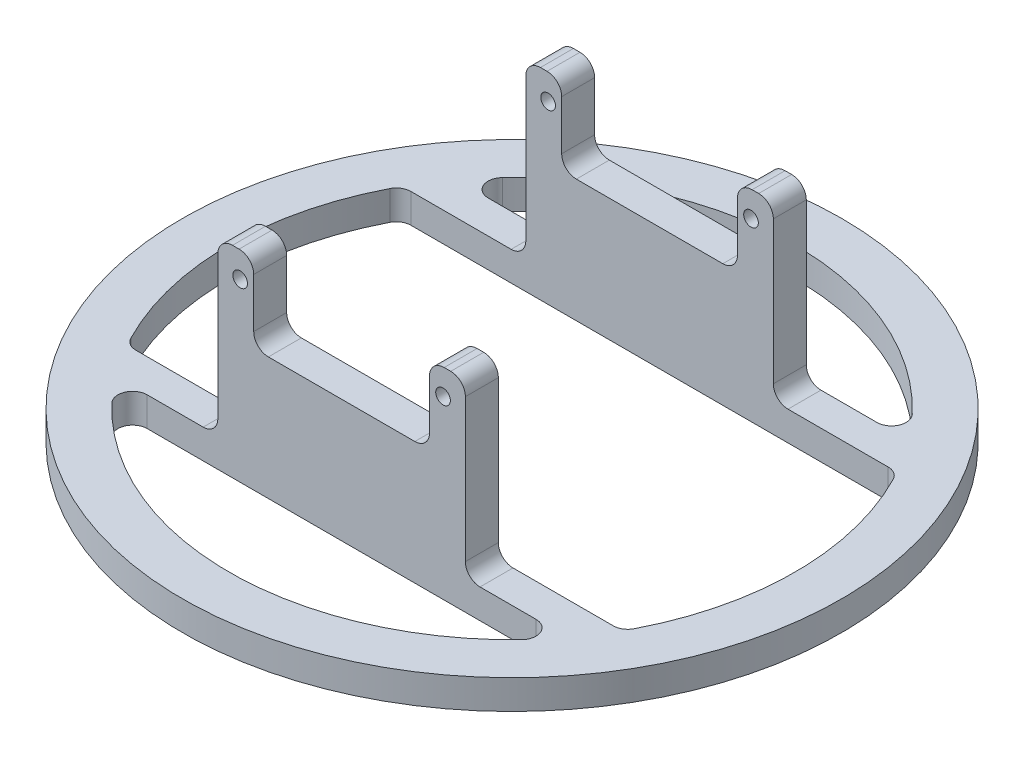
SolidWorks part; units mm, degrees
ref_plane "Front Plane" through (0, 0, 0) normal (0, 0, 1) x (1, 0, 0)
ref_plane "Top Plane" through (0, 0, 0) normal (0, 1, 0) x (1, 0, 0)
ref_plane "Right Plane" through (0, 0, 0) normal (1, 0, 0) x (0, 0, -1)
sketch "Sketch1" plane through (0, 0, 0) normal (0, 0, 1) x (1, 0, 0)
  line L0 (-13.85, 0) -> (13.85, 0) construction
  line L1 (-12, -6.25) -> (-12, 6.25) construction
  line L2 (15.9, -6.25) -> (-15.9, -6.25) construction
  line L3 (15.9, -6.25) -> (15.9, 6.25) construction
  line L4 (15.9, 6.25) -> (-15.9, 6.25) construction
  line L5 (-15.9, -6.25) -> (-15.9, 6.25) construction
  line L6 (12, 3.5) -> (16.9, 3.5)
  line L7 (12, 3.5) -> (12, -7.25)
  line L8 (11.5, -6.25) -> (-11.5, -6.25) construction
  line L9 (11.5, -6.25) -> (11.5, 6.25) construction
  line L10 (11.5, 6.25) -> (-11.5, 6.25) construction
  line L11 (-11.5, -6.25) -> (-11.5, 6.25) construction
  line L12 (16.9, 3.5) -> (16.9, -20)
  line L14 (-12, 3.5) -> (-16.9, 3.5)
  line L15 (-16.9, 3.5) -> (-16.9, -20)
  line L16 (-16.9, -20) -> (16.9, -20)
  line L17 (0, -20) -> (0, 0) construction
  line L18 (-12, 3.5) -> (-12, -7.25)
  line L19 (-12, -7.25) -> (12, -7.25)
  circle A0 centre (13.85, 0) radius 1
  circle A1 centre (-13.85, 0) radius 1
  point P5 (0, 0)
  point P6 (0, 0)
  point P20 (-17.0505, 3.2413)
  point P25 (-11.5, -2.8583)
  point P26 (-11.5, -6.25)
  point P31 (0, -7.25)
  dimension "D1" = 2
  dimension "D2" = 27.7
  dimension "D3" = 12.5
  dimension "D4" = 31.8
  dimension "D5" = 23
  dimension "D6" = 0.5
  dimension "D7" = 1
  dimension "D8" = 1
  dimension "D9" = 3.5
  dimension "D10" = 20
extrude "Boss-Extrude1" add sketch "Sketch1" along normal blind 4.5
ref_plane "Plane1" through (0, 0, -15.6) normal (0, 0, -1) x (-1, 0, 0)
ref_plane "Plane2" through (0, 0, -21.95) normal (0, 0, -1) x (-1, 0, 0)
ref_plane "Plane3" through (0, 0, -18.775) normal (0, 0, -1) x (-1, 0, 0)
ref_plane "Plane4" through (0, -20, 0) normal (0, -1, 0) x (-1, 0, 0)
sketch "Sketch4" plane through (0, -20, 0) normal (0, -1, 0) x (-1, 0, 0)
  line L0 (0, 0) -> (0, 18.775) construction
  line L1 (55, 18.775) -> (-55, 18.775) construction
  line L2 (16.9, -4.5) -> (16.9, 0) construction
  line L3 (16.9, -4.5) -> (-16.9, -4.5) construction
  line L4 (-16.9, -4.5) -> (-16.9, 0) construction
  line L5 (16.9, 0) -> (-16.9, 0) construction
  line L6 (16.9, -4.5) -> (16.9, 0) construction
  line L7 (16.9, -4.5) -> (-16.9, -4.5) construction
  line L8 (-16.9, -4.5) -> (-16.9, 0) construction
  line L9 (16.9, 0) -> (-16.9, 0) construction
  line L10 (-33.7835, 0) -> (33.7835, 0)
  line L11 (-30.8561, -4.5) -> (30.8561, -4.5)
  line L12 (-38.65, 18.775) -> (38.65, 18.775) construction
  line L13 (-30.8561, 42.05) -> (30.8561, 42.05)
  line L14 (-33.7835, 37.55) -> (33.7835, 37.55)
  circle A0 centre (0, 18.775) radius 45
  arc A1 (30.8561, 42.05) -> (-30.8561, 42.05) centre (0, 18.775) ccw
  arc A2 (-33.7835, 37.55) -> (-33.7835, 0) centre (0, 18.775) ccw
  arc A3 (-30.8561, -4.5) -> (30.8561, -4.5) centre (0, 18.775) ccw
  arc A4 (33.7835, 0) -> (33.7835, 37.55) centre (0, 18.775) ccw
  dimension "D1" = 90
  dimension "D2" = 6.35
sketch "Sketch2" plane through (0, -20, 0) normal (0, -1, 0) x (-1, 0, 0)
  line L0 (0, 0) -> (0, 18.775) construction
  line L1 (55, 18.775) -> (-55, 18.775) construction
  line L2 (-16.9, -4.5) -> (-16.9, 0) construction
  line L3 (-16.9, -4.5) -> (-16.9, 0)
  line L4 (16.9, -4.5) -> (-16.9, -4.5) construction
  line L5 (16.9, -4.5) -> (16.9, 0) construction
  line L6 (16.9, -4.5) -> (-16.9, -4.5)
  line L7 (16.9, -4.5) -> (16.9, 0)
  line L8 (0, 18.775) -> (28.7634, 18.775) construction
  line L9 (16.9, 42.05) -> (-16.9, 42.05)
  circle A0 centre (0, 18.775) radius 28.7634
  point P9 (0, 0)
extrude "Boss-Extrude3" add sketch "Sketch4" along normal blind 4
mirror "Mirror2" about plane through (0, 0, -18.775) normal (0, 0, -1) of "Boss-Extrude1"
fillet "Fillet2" radius 2 12 edges at (-12, -7.25, -39.8) (12, -7.25, -39.8) (-12, -7.25, 2.25) (12, -7.25, 2.25) (-33.7835, -22, 0) (-33.7835, -22, -37.55) (30.8561, -22, 4.5) (-30.8561, -22, 4.5) (33.7835, -22, 0) (33.7835, -22, -37.55) (30.8561, -22, -42.05) (-30.8561, -22, -42.05)
fillet "Fillet3" radius 2 12 edges at (-16.9, 3.5, 2.25) (-12, 3.5, 2.25) (12, 3.5, 2.25) (16.9, 3.5, 2.25) (-16.9, 3.5, -39.8) (-12, 3.5, -39.8) (12, 3.5, -39.8) (16.9, 3.5, -39.8) (16.9, -20, 2.25) (-16.9, -20, 2.25) (-16.9, -20, -39.8) (16.9, -20, -39.8)
